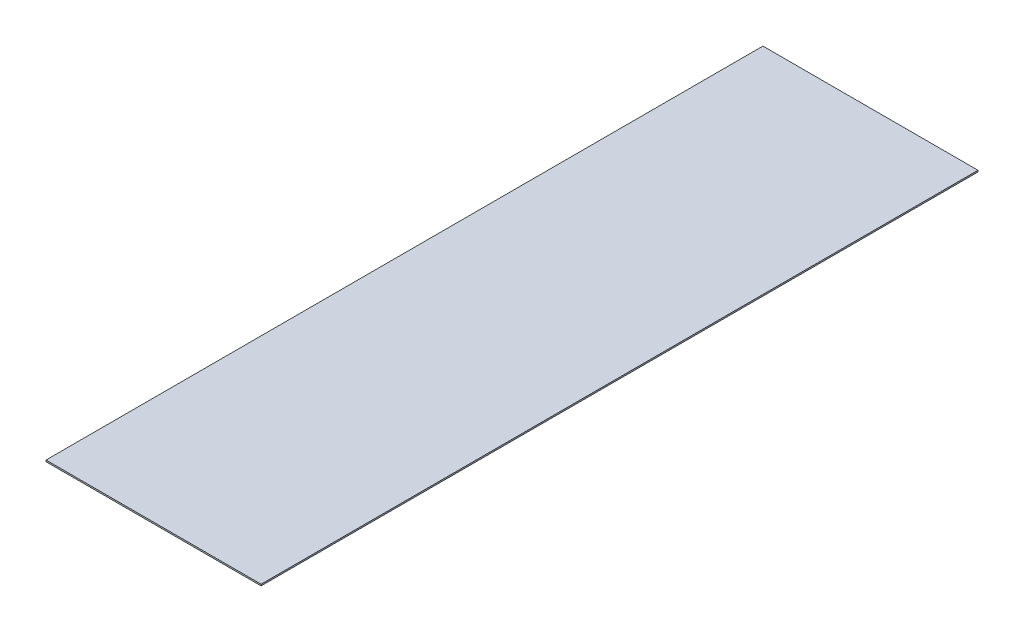
SolidWorks part; units mm, degrees
material "ASTM A36 Acero"
ref_plane "Alzado" through (0, 0, 0) normal (0, 0, 1) x (1, 0, 0)
ref_plane "Planta" through (0, 0, 0) normal (0, 1, 0) x (1, 0, 0)
ref_plane "Vista lateral" through (0, 0, 0) normal (1, 0, 0) x (0, 0, -1)
sketch "Croquis1" plane through (0, 0, 0) normal (0, 1, 0) x (1, 0, 0)
  line L1 (-457.2, -1524) -> (457.2, -1524)
  line L2 (-457.2, -1524) -> (-457.2, 1524)
  line L3 (-457.2, 1524) -> (457.2, 1524)
  line L4 (457.2, -1524) -> (457.2, 1524)
  line L5 (-457.2, -1524) -> (457.2, 1524) construction
  line L6 (-457.2, 1524) -> (457.2, -1524) construction
  point P0 (0, 0)
  dimension "D1" = 3048
  dimension "D2" = 914.4
extrude "Saliente-Extruir1" add sketch "Croquis1" along normal blind 6.4
